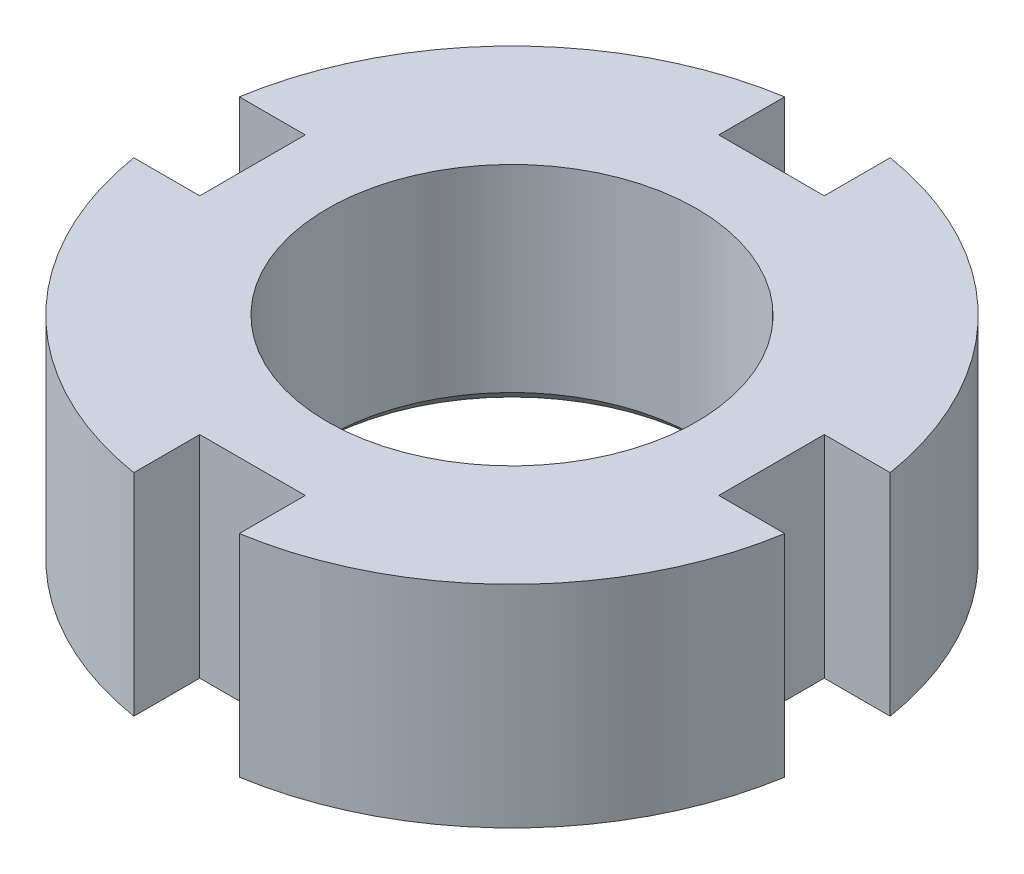
SolidWorks part; units mm, degrees
ref_plane "Front Plane" through (0, 0, 0) normal (0, 0, 1) x (1, 0, 0)
ref_plane "Top Plane" through (0, 0, 0) normal (0, 1, 0) x (1, 0, 0)
ref_plane "Right Plane" through (0, 0, 0) normal (1, 0, 0) x (0, 0, -1)
sketch "Sketch1" plane through (0, 0, 0) normal (0, 1, 0) x (1, 0, 0)
  line L0 (0, 0) -> (40.1571, 0) construction
  line L1 (-4, -19.6779) -> (-4, -24.6779)
  line L2 (19.6779, 4) -> (24.6779, 4)
  line L3 (19.6779, 4) -> (19.6779, -4)
  line L4 (19.6779, -4) -> (24.6779, -4)
  line L6 (4, -19.6779) -> (-4, -19.6779)
  line L7 (4, -19.6779) -> (4, -24.6779)
  line L8 (-19.6779, 4) -> (-24.6779, 4)
  line L9 (-19.6779, -4) -> (-19.6779, 4)
  line L10 (-19.6779, -4) -> (-24.6779, -4)
  line L11 (4, 19.6779) -> (4, 24.6779)
  line L12 (-4, 19.6779) -> (4, 19.6779)
  line L13 (-4, 19.6779) -> (-4, 24.6779)
  arc A0 (-4, 24.6779) -> (-24.6779, 4) centre (0, 0) ccw
  arc A1 (24.6779, 4) -> (4, 24.6779) centre (0, 0) ccw
  arc A2 (4, -24.6779) -> (24.6779, -4) centre (0, 0) ccw
  arc A3 (-24.6779, -4) -> (-4, -24.6779) centre (0, 0) ccw
  point P7 (0, 0)
  point P23 (0, 0)
  dimension "D1" = 50
  dimension "D2" = 8
  dimension "D3" = 5
  dimension "D4" = 4
extrude "Boss-Extrude1" add sketch "Sketch1" along normal mid plane 16
hole_wizard "M30x2.0 Tapped Hole1" positions "Sketch2" profile "Sketch3" tap size "M30x2.0" standard "ANSI Metric"
sketch "Sketch2" plane through (0, -8, 0) normal (0, -1, 0) x (-1, 0, 0)
  point P0 (0, 0)
sketch "Sketch3" plane through (0, -8, 0) normal (1, 0, 0) x (0, 0, -1)
  line L0 (0, 0) -> (0, 24.412)
  line L1 (0, 24.412) -> (14, 16)
  line L2 (14, 16) -> (14, 1.025)
  line L3 (14, 1.025) -> (15.025, 0)
  line L5 (15.025, 0) -> (0, 0)
  line L6 (-14, 1.025) -> (-15.025, 0) construction
  line L10 (0, 24.412) -> (-14, 16) construction
  line L11 (0, -6.35) -> (0, 107.95) construction
  dimension "Tap Drill Dia." = 28
  dimension "Tap Drill Depth" = 16
  dimension "Near C'Sink Dia." = 30.05
  dimension "Near C'Sink Angle" = 90
  dimension "Drill Angle" = 118
cosmetic thread "Hole Thread1" parameters "D1"=10, "D2"=30
